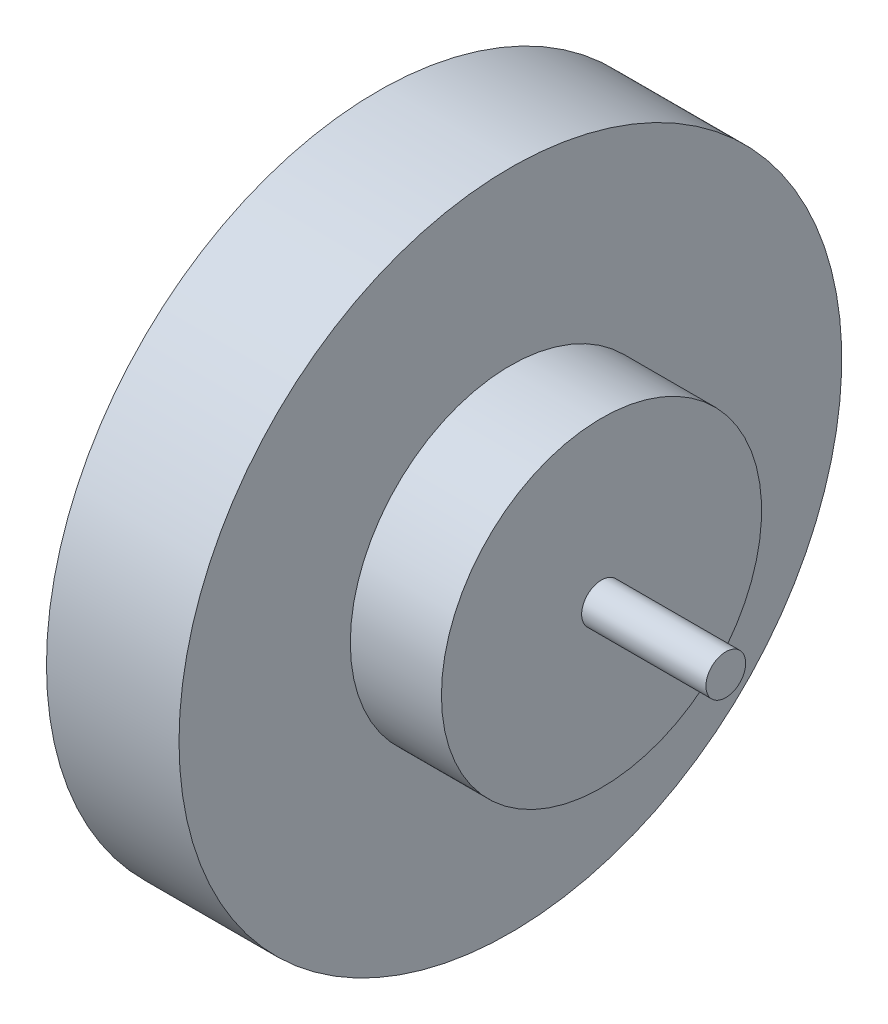
SolidWorks part; units mm, degrees
ref_plane "前视基准面" through (0, 0, 0) normal (0, 0, 1) x (1, 0, 0)
ref_plane "上视基准面" through (0, 0, 0) normal (0, 1, 0) x (1, 0, 0)
ref_plane "右视基准面" through (0, 0, 0) normal (1, 0, 0) x (0, 0, -1)
sketch "草图1" plane through (0, 0, 0) normal (0, 0, 1) x (1, 0, 0)
  line L0 (0, -1219.9437) -> (0, 59777.2418) construction
  line L1 (-1219.9437, 0) -> (59777.2418, 0) construction
  line L2 (0, 0) -> (0, 100)
  line L3 (0, 100) -> (20, 100)
  line L4 (20, 100) -> (20, 48.3087)
  line L5 (20, 48.3087) -> (47.5, 48.3087)
  line L6 (47.5, 48.3087) -> (47.5, 6)
  line L7 (47.5, 6) -> (85, 6)
  line L8 (85, 6) -> (85, 0)
  line L9 (85, 0) -> (0, 0)
  dimension "D1" = 100
  dimension "D2" = 85
  dimension "D3" = 47.5
  dimension "D4" = 6
  dimension "D5" = 20
revolve "旋转1" add sketch "草图1" angle 360 about L1
mirror "镜向1" about plane through (0, 0, 0) normal (1, 0, 0) of "旋转1"
